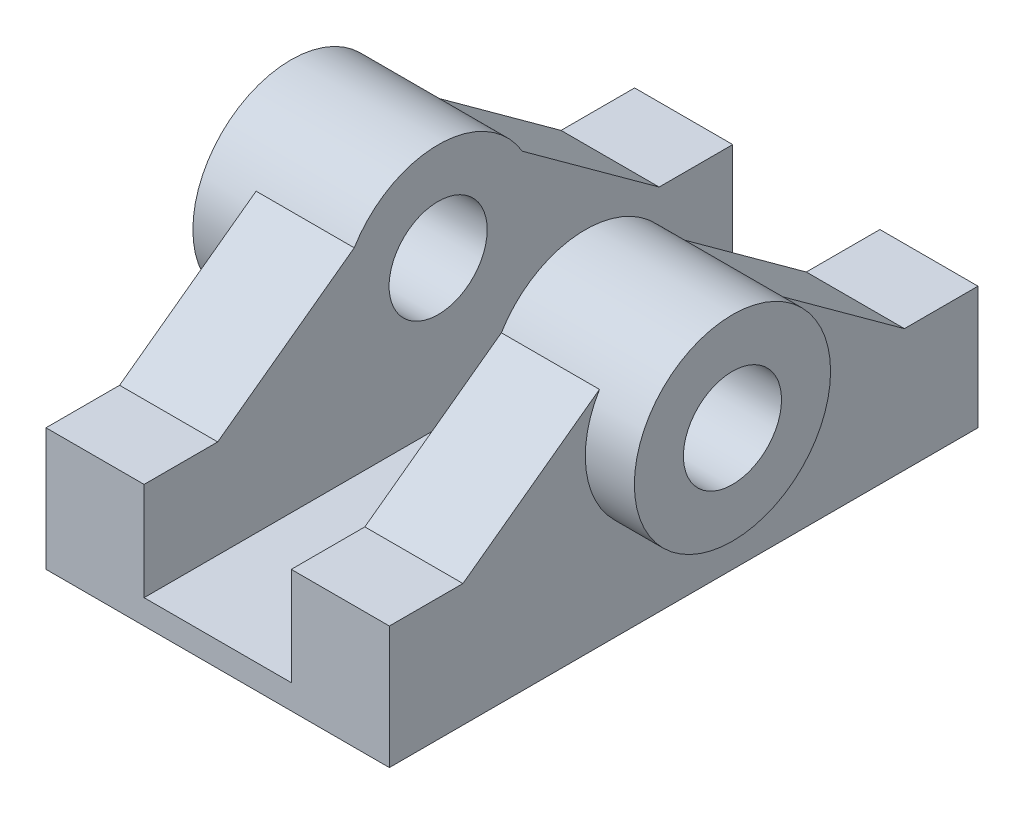
SolidWorks part; units mm, degrees
ref_plane "Front Plane" through (0, 0, 0) normal (0, 0, 1) x (1, 0, 0)
ref_plane "Top Plane" through (0, 0, 0) normal (0, 1, 0) x (1, 0, 0)
ref_plane "Right Plane" through (0, 0, 0) normal (1, 0, 0) x (0, 0, -1)
sketch "Sketch1" plane through (0, 0, 0) normal (1, 0, 0) x (0, 0, -1)
  line L0 (-55.1545, 0) -> (-55.1545, 25)
  line L1 (-55.1545, 25) -> (-40.1545, 25)
  line L2 (-40.1545, 25) -> (-12.3212, 45.3555)
  line L3 (-55.1545, 0) -> (64.8455, 0)
  line L4 (64.8455, 0) -> (64.8455, 25)
  line L5 (64.8455, 25) -> (49.8455, 25)
  line L6 (49.8455, 25) -> (21.9505, 45.2708)
  circle A0 centre (4.7892, 35) radius 20
  circle A1 centre (4.7892, 35) radius 10
  dimension "D5" = 40
  dimension "D1" = 120
  dimension "D2" = 15
  dimension "D3" = 25
  dimension "D4" = 35
extrude "Boss-Extrude2" add sketch "Sketch1" against normal blind 20 contours A0 L2 L1 L0 L3 L4 L5 L6 | A0 A1
sketch "Sketch2" plane through (0, 0, 0) normal (1, 0, 0) x (0, 0, -1)
  circle A0 centre (4.7892, 35) radius 20
  circle A1 centre (4.7892, 35) radius 10
extrude "Boss-Extrude3" add sketch "Sketch2" along normal blind 10
sketch "Sketch3" plane through (0, 0, 55.1545) normal (0, 0, 1) x (1, 0, 0)
  line L0 (-20, 0) -> (-35, 0)
  line L1 (-35, 0) -> (-35, 5)
  line L2 (-35, 5) -> (-20, 5)
  line L3 (-20, 0) -> (-20, 25) construction
  line L4 (-20, 5) -> (-20, 0)
  dimension "D1" = 5
  dimension "D2" = 15
extrude "Boss-Extrude4" add sketch "Sketch3" against normal blind 120
ref_plane "Plane1" through (-35, 0, 0) normal (-1, 0, 0) x (0, 0, 1)
mirror "Mirror1" about plane through (-35, 0, 0) normal (-1, 0, 0) of bodies 104
